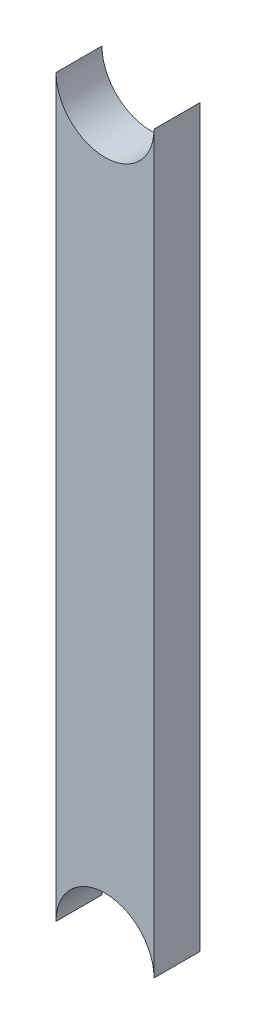
SolidWorks part; units mm, degrees
ref_plane "Front Plane" through (0, 0, 0) normal (0, 0, 1) x (1, 0, 0)
ref_plane "Top Plane" through (0, 0, 0) normal (0, 1, 0) x (1, 0, 0)
ref_plane "Right Plane" through (0, 0, 0) normal (1, 0, 0) x (0, 0, -1)
sketch "Sketch1" plane through (0, 0, 0) normal (0, 0, 1) x (1, 0, 0)
  line L1 (-3.2, 0) -> (-3.2, 48)
  line L2 (3.2, 48) -> (3.2, 0)
  line L3 (0, -2.75) -> (0, 2.75) construction
  arc A2 (3.2, 0) -> (-3.2, 0) centre (0, 0) ccw
  arc A3 (-3.2, 48) -> (3.2, 48) centre (0, 48) ccw
  dimension "D1" = 6.4
  dimension "D2" = 48
extrude "Boss-Extrude3" add sketch "Sketch1" along normal blind 3
equation "\"bScale\"= 8"
equation "\"D1@Sketch2\"= \"bScale\" * 0.8"
equation "\"D2@Sketch2\"= \"bScale\" * 0.6"
equation "\"lScale\"= 8"
equation "\"D2@Sketch1\"= 6 * \"lScale\""
equation "\"D1@Sketch1\"=0.8 * \"bScale\""
